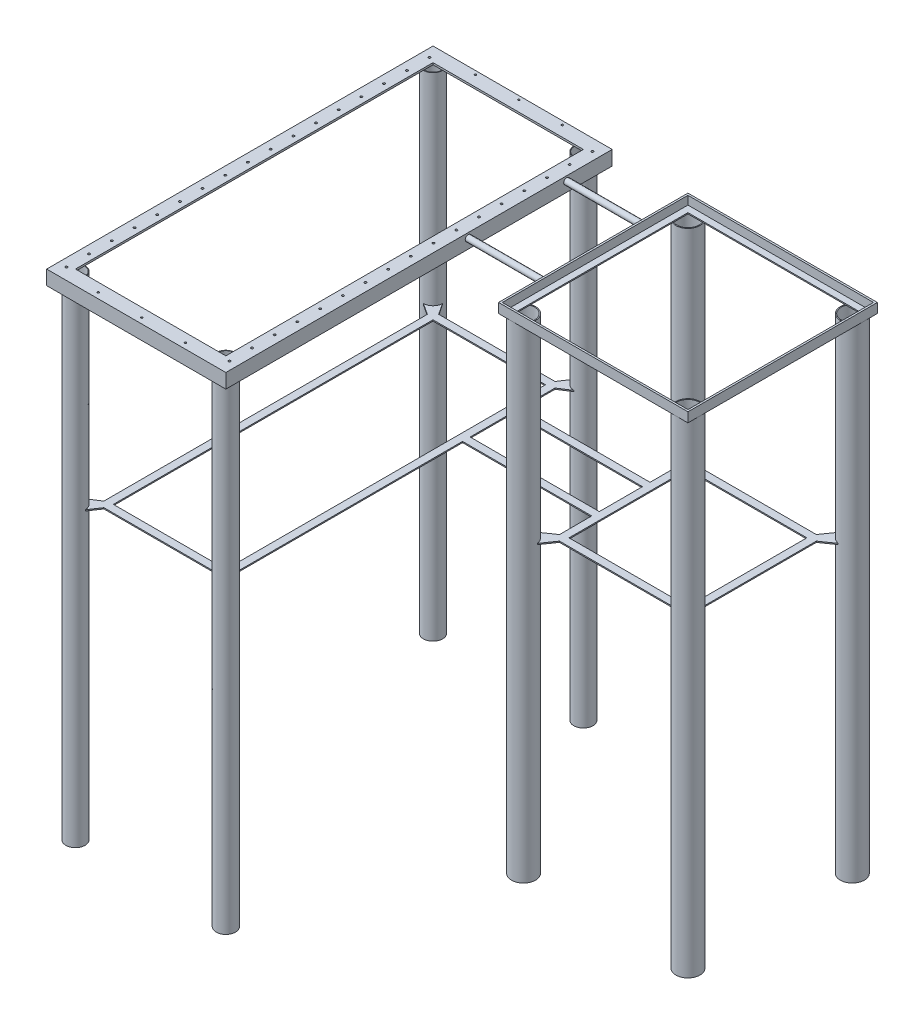
SolidWorks part; units mm, degrees
ref_plane "Alzado" through (0, 0, 0) normal (0, 0, 1) x (1, 0, 0)
ref_plane "Planta" through (0, 0, 0) normal (0, 1, 0) x (1, 0, 0)
ref_plane "Vista lateral" through (0, 0, 0) normal (1, 0, 0) x (0, 0, -1)
sketch "Croquis1" plane through (0, 0, 0) normal (0, 1, 0) x (1, 0, 0)
  line L0 (236.5, 510) -> (-236.5, -510) construction
  line L1 (-236.5, 510) -> (236.5, 510)
  line L2 (-236.5, 510) -> (-236.5, -510)
  line L3 (-236.5, -510) -> (236.5, -510)
  line L4 (236.5, 510) -> (236.5, -510)
  line L6 (-198.5, 472) -> (198.5, 472)
  line L7 (-198.5, 472) -> (-198.5, -472)
  line L8 (-198.5, -472) -> (198.5, -472)
  line L9 (198.5, 472) -> (198.5, -472)
  dimension "D1" = 473
  dimension "D2" = 1020
  dimension "D3" = 38
  dimension "D4" = 38
  dimension "D5" = 38
  dimension "D6" = 38
extrude "Saliente-Extruir1" add sketch "Croquis1" along normal blind 5
sketch "Croquis2" plane through (0, 0, 0) normal (0, -1, 0) x (1, 0, 0)
  line L0 (-231.5, 505) -> (231.5, 505)
  line L1 (231.5, 505) -> (231.5, -505)
  line L2 (231.5, -505) -> (-231.5, -505)
  line L3 (-231.5, -505) -> (-231.5, 505)
  line L4 (-236.5, 510) -> (236.5, 510) construction
  line L5 (-236.5, -510) -> (-236.5, 510) construction
  line L6 (236.5, 510) -> (236.5, -510) construction
  line L7 (236.5, -510) -> (-236.5, -510) construction
  line L8 (-236.5, 510) -> (236.5, 510)
  line L9 (-236.5, -510) -> (-236.5, 510)
  line L10 (236.5, 510) -> (236.5, -510)
  line L11 (236.5, -510) -> (-236.5, -510)
  dimension "D1" = 5
extrude "Saliente-Extruir2" add sketch "Croquis2" along normal blind 33
sketch "Croquis3" plane through (0, 0, 0) normal (0, -1, 0) x (1, 0, 0)
  line L0 (0, -505) -> (0, -413.6353) construction
  line L1 (-231.5, -505) -> (231.5, -505) construction
  line L2 (198.5, 0) -> (-198.5, 0) construction
  line L3 (198.5, 472) -> (198.5, -472) construction
  line L4 (-198.5, -472) -> (-198.5, 472) construction
  circle A0 centre (-198.5, -472) radius 25.4
  circle A1 centre (-198.5, -472) radius 23.9
  circle A2 centre (198.5, -472) radius 23.9
  circle A3 centre (198.5, -472) radius 25.4
  circle A4 centre (-198.5, 472) radius 25.4
  circle A5 centre (-198.5, 472) radius 23.9
  circle A6 centre (198.5, 472) radius 23.9
  circle A7 centre (198.5, 472) radius 25.4
  dimension "D1" = 50.8
  dimension "D2" = 47.8
extrude "Saliente-Extruir3" add sketch "Croquis3" along normal blind 1300
sketch "Croquis4" plane through (0, 0, 0) normal (0, -1, 0) x (1, 0, 0)
  line L0 (236.5, 510) -> (-236.5, 510) construction
  line L1 (-236.5, 510) -> (-236.5, -510) construction
  line L2 (236.5, -510) -> (236.5, 510) construction
  line L12 (168.5, 442) -> (168.5, -442)
  line L13 (168.5, -442) -> (-168.5, -442)
  line L14 (-168.5, -442) -> (-168.5, 442)
  line L15 (-168.5, 442) -> (168.5, 442)
  line L16 (168.5, 442) -> (-168.5, -442) construction
  line L18 (148.5, 422) -> (-148.5, 422)
  line L19 (148.5, 422) -> (148.5, -422)
  line L20 (-236.5, -510) -> (236.5, -510) construction
  line L21 (148.5, -422) -> (-148.5, -422)
  line L22 (-148.5, 422) -> (-148.5, -422)
  dimension "D1" = 68
  dimension "D2" = 20
  dimension "D3" = 68
  dimension "D4" = 68
  dimension "D5" = 68
  dimension "D6" = 20
  dimension "D7" = 20
  dimension "D8" = 20
extrude "Saliente-Extruir4" add sketch "Croquis4" along normal blind 3 from offset 533 separate body
sketch "Croquis5" plane through (0, -533, 0) normal (0, 1, 0) x (1, 0, 0)
  line L0 (153.5, 442) -> (173.1118, 471.2271)
  line L1 (-168.5, 442) -> (168.5, 442) construction
  line L2 (173.1118, 471.2271) -> (181.9129, 457.7456)
  line L3 (181.9129, 457.7456) -> (198.523, 446.6)
  line L4 (198.523, 446.6) -> (168.5, 427)
  line L5 (168.5, 442) -> (168.5, -442) construction
  line L6 (168.5, 427) -> (168.5, 442)
  line L7 (168.5, 442) -> (153.5, 442)
  line L8 (0, 442) -> (0, 371.6421) construction
  line L9 (-168.5, 0) -> (-86.6716, 0) construction
  line L10 (-168.5, -442) -> (-168.5, 442) construction
  line L11 (-198.523, 446.6) -> (-168.5, 427)
  line L12 (-181.9129, 457.7456) -> (-198.523, 446.6)
  line L13 (-173.1118, 471.2271) -> (-181.9129, 457.7456)
  line L14 (-168.5, 427) -> (-168.5, 442)
  line L15 (-168.5, 442) -> (-153.5, 442)
  line L16 (-153.5, 442) -> (-173.1118, 471.2271)
  line L17 (168.5, -442) -> (153.5, -442)
  line L18 (168.5, -427) -> (168.5, -442)
  line L19 (198.523, -446.6) -> (168.5, -427)
  line L20 (181.9129, -457.7456) -> (198.523, -446.6)
  line L21 (173.1118, -471.2271) -> (181.9129, -457.7456)
  line L22 (153.5, -442) -> (173.1118, -471.2271)
  line L23 (-153.5, -442) -> (-173.1118, -471.2271)
  line L24 (-168.5, -442) -> (-153.5, -442)
  line L25 (-168.5, -427) -> (-168.5, -442)
  line L26 (-173.1118, -471.2271) -> (-181.9129, -457.7456)
  line L27 (-181.9129, -457.7456) -> (-198.523, -446.6)
  line L28 (-198.523, -446.6) -> (-168.5, -427)
  arc A0 (173.1, 472) -> (198.5, 446.6) centre (198.5, 472) ccw construction
  dimension "D1" = 15
  dimension "D2" = 15
  dimension "D3" = 16.1
  dimension "D4" = 67
  dimension "D5" = 67
extrude "Saliente-Extruir5" add sketch "Croquis5" against normal blind 3
sketch "Croquis6" plane through (0, 5, 0) normal (0, 1, 0) x (1, 0, 0)
  line L0 (936.5, 510) -> (436.5, 10) construction
  line L1 (436.5, 510) -> (936.5, 510)
  line L2 (436.5, 510) -> (436.5, 10)
  line L3 (436.5, 10) -> (936.5, 10)
  line L4 (936.5, 510) -> (936.5, 10)
  line L5 (-236.5, -510) -> (236.5, -510) construction
  line L7 (458.725, 487.775) -> (914.275, 487.775)
  line L8 (458.725, 487.775) -> (458.725, 32.225)
  line L9 (458.725, 32.225) -> (914.275, 32.225)
  line L10 (914.275, 487.775) -> (914.275, 32.225)
  dimension "D1" = 200
  dimension "D2" = 500
  dimension "D3" = 500
  dimension "D4" = 520
  dimension "D5" = 22.225
  dimension "D6" = 22.225
  dimension "D7" = 22.225
  dimension "D8" = 22.225
extrude "Saliente-Extruir6" add sketch "Croquis6" against normal blind 3 from offset 22.225 separate body
sketch "Croquis7" plane through (0, -20.225, 0) normal (0, -1, 0) x (1, 0, 0)
  line L0 (436.5, -510) -> (436.5, -10) construction
  line L1 (436.5, -10) -> (936.5, -10) construction
  line L2 (936.5, -10) -> (936.5, -510) construction
  line L3 (936.5, -510) -> (436.5, -510) construction
  line L4 (436.5, -510) -> (436.5, -10)
  line L5 (436.5, -10) -> (936.5, -10)
  line L6 (936.5, -10) -> (936.5, -510)
  line L7 (936.5, -510) -> (436.5, -510)
  line L8 (441.5, -505) -> (441.5, -15)
  line L9 (441.5, -15) -> (931.5, -15)
  line L10 (931.5, -15) -> (931.5, -505)
  line L11 (931.5, -505) -> (441.5, -505)
  dimension "D1" = 5
extrude "Saliente-Extruir7" add sketch "Croquis7" against normal blind 25.4
sketch "Croquis9" plane through (436.5, 0, 0) normal (-1, 0, 0) x (0, 0, 1)
  line L0 (-510, -7.525) -> (-10, -7.525) construction
  line L1 (-510, -20.225) -> (-510, 5.175) construction
  line L2 (-10, -20.225) -> (-10, 5.175) construction
  circle A0 centre (-390, -7.525) radius 7.9375
  circle A1 centre (-130, -7.525) radius 7.9375
  dimension "D1" = 15.875
  dimension "D2" = 15.875
  dimension "D3" = 120
  dimension "D4" = 120
extrude "Saliente-Extruir8" add sketch "Croquis9" along normal up to next
sketch "Croquis10" plane through (0, -20.225, 0) normal (0, -1, 0) x (1, 0, 0)
  line L0 (469.5, -10) -> (469.5, -43) construction
  line L1 (436.5, -10) -> (936.5, -10) construction
  line L2 (469.5, -43) -> (436.5, -43) construction
  line L3 (436.5, -510) -> (436.5, -10) construction
  line L4 (458.725, -260) -> (524.3581, -260) construction
  line L5 (458.725, -487.775) -> (458.725, -32.225) construction
  line L7 (914.275, -487.775) -> (458.725, -487.775) construction
  line L8 (686.5, -487.775) -> (686.5, -390.923) construction
  circle A0 centre (469.5, -43) radius 31.75
  circle A1 centre (469.5, -477) radius 31.75
  circle A2 centre (903.5, -477) radius 31.75
  circle A3 centre (903.5, -43) radius 31.75
  circle A4 centre (469.5, -43) radius 29.25
  circle A5 centre (469.5, -477) radius 29.25
  circle A6 centre (903.5, -477) radius 29.25
  circle A7 centre (903.5, -43) radius 29.25
  dimension "D3" = 63.5
  dimension "D4" = 58.5
  dimension "D1" = 33
  dimension "D2" = 33
extrude "Saliente-Extruir9" add sketch "Croquis10" along normal up to surface (1279.775 mm away) up to face at (198.5, -1300, -446.6)
sketch "Croquis11" plane through (0, -533, 0) normal (0, 1, 0) x (1, 0, 0)
  line L1 (469.5, 477) -> (903.5, 477) construction
  line L2 (469.5, 477) -> (469.5, 43) construction
  line L3 (469.5, 43) -> (903.5, 43) construction
  line L4 (903.5, 477) -> (903.5, 43) construction
  line L5 (509.5, 437) -> (863.5, 437)
  line L6 (509.5, 437) -> (509.5, 83)
  line L7 (509.5, 83) -> (863.5, 83)
  line L8 (863.5, 437) -> (863.5, 83)
  line L9 (529.5, 417) -> (843.5, 417)
  line L10 (529.5, 417) -> (529.5, 103)
  line L11 (529.5, 103) -> (843.5, 103)
  line L12 (843.5, 417) -> (843.5, 103)
  dimension "D1" = 40
  dimension "D2" = 40
  dimension "D3" = 40
  dimension "D4" = 20
  dimension "D5" = 20
  dimension "D6" = 20
  dimension "D7" = 20
extrude "Saliente-Extruir10" add sketch "Croquis11" against normal up to vertex (3 mm away) separate body
sketch "Croquis12" plane through (0, -533, 0) normal (0, 1, 0) x (1, 0, 0)
  line L0 (509.5, 422) -> (475.0956, 446.0902)
  line L1 (509.5, 437) -> (509.5, 83) construction
  line L2 (475.0956, 446.0902) -> (491.3466, 453.9611)
  line L3 (491.3466, 453.9611) -> (500.4098, 471.4044)
  line L4 (500.4098, 471.4044) -> (524.5, 437)
  line L5 (863.5, 437) -> (509.5, 437) construction
  line L6 (524.5, 437) -> (509.5, 437)
  line L7 (509.5, 437) -> (509.5, 422)
  line L8 (686.5, 417) -> (686.5, 340.5834) construction
  line L9 (843.5, 417) -> (529.5, 417) construction
  line L10 (863.5, 437) -> (863.5, 422)
  line L11 (529.5, 417) -> (529.5, 103) construction
  line L12 (529.5, 260) -> (598.9729, 260) construction
  line L13 (848.5, 437) -> (863.5, 437)
  line L14 (872.5902, 471.4044) -> (848.5, 437)
  line L15 (881.6534, 453.9611) -> (872.5902, 471.4044)
  line L16 (897.9044, 446.0902) -> (881.6534, 453.9611)
  line L17 (863.5, 422) -> (897.9044, 446.0902)
  line L18 (863.5, 98) -> (897.9044, 73.9098)
  line L19 (897.9044, 73.9098) -> (881.6534, 66.0389)
  line L20 (881.6534, 66.0389) -> (872.5902, 48.5956)
  line L21 (872.5902, 48.5956) -> (848.5, 83)
  line L22 (848.5, 83) -> (863.5, 83)
  line L23 (863.5, 83) -> (863.5, 98)
  line L24 (509.5, 83) -> (509.5, 98)
  line L25 (524.5, 83) -> (509.5, 83)
  line L26 (500.4098, 48.5956) -> (524.5, 83)
  line L27 (491.3466, 66.0389) -> (500.4098, 48.5956)
  line L28 (475.0956, 73.9098) -> (491.3466, 66.0389)
  line L29 (509.5, 98) -> (475.0956, 73.9098)
  line L30 (168.5, 427) -> (168.5, -427) construction
  line L31 (168.5, 337) -> (509.5, 337)
  line L32 (168.5, 337) -> (168.5, 317)
  line L33 (168.5, 317) -> (509.5, 317)
  line L34 (509.5, 337) -> (509.5, 317)
  line L36 (168.5, 203) -> (509.5, 203)
  line L37 (168.5, 203) -> (168.5, 183)
  line L38 (168.5, 183) -> (509.5, 183)
  line L39 (509.5, 203) -> (509.5, 183)
  line L40 (529.5, 103) -> (843.5, 103) construction
  circle A0 centre (469.5, 477) radius 31.75 construction
  dimension "D1" = 55
  dimension "D2" = 55
  dimension "D3" = 42
  dimension "D4" = 42
  dimension "D5" = 15
  dimension "D6" = 15
  dimension "D7" = 20
  dimension "D8" = 20
  dimension "D9" = 80
  dimension "D10" = 80
extrude "Saliente-Extruir11" add sketch "Croquis12" against normal up to vertex
sketch "Esboço1" plane through (0, 5, 0) normal (0, 1, 0) x (1, 0, 0)
  circle A0 centre (-114.9881, -495.2375) radius 2.5
  circle A1 centre (0.0119, -495.2375) radius 2.5
  circle A2 centre (115.0119, -495.2375) radius 2.5
  circle A3 centre (-114.9881, 500.2375) radius 2.5
  circle A4 centre (0.0119, 500.2375) radius 2.5
  circle A5 centre (115.0119, 500.2375) radius 2.5
  dimension "D1" = 5
  dimension "D2" = 5
  dimension "D3" = 5
  dimension "D4" = 5
  dimension "D5" = 5
  dimension "D6" = 5
extrude "Corte-extrusão1" cut sketch "Esboço1" against normal up to next
sketch "Esboço2" plane through (0, 5, 0) normal (0, 1, 0) x (1, 0, 0)
  line L1 (0, -510) -> (0, -370.7931) construction
  line L2 (-236.5, -510) -> (236.5, -510) construction
  circle A0 centre (215.04, -479.28) radius 2.87
  circle A1 centre (215.04, -419.37) radius 2.87
  circle A2 centre (215.04, -359.46) radius 2.87
  circle A3 centre (215.04, -299.55) radius 2.87
  circle A4 centre (215.04, -239.64) radius 2.87
  circle A5 centre (215.04, -179.73) radius 2.87
  circle A6 centre (215.04, -119.82) radius 2.87
  circle A7 centre (215.04, -59.91) radius 2.87
  circle A8 centre (215.04, 0) radius 2.87
  circle A9 centre (215.04, 59.91) radius 2.87
  circle A10 centre (215.04, 119.82) radius 2.87
  circle A11 centre (215.04, 179.73) radius 2.87
  circle A12 centre (215.04, 239.64) radius 2.87
  circle A13 centre (215.04, 299.55) radius 2.87
  circle A14 centre (215.04, 359.46) radius 2.87
  circle A15 centre (215.04, 419.37) radius 2.87
  circle A16 centre (215.04, 479.28) radius 2.87
  circle A17 centre (-215.04, -239.64) radius 2.87
  circle A18 centre (-215.04, -299.55) radius 2.87
  circle A19 centre (-215.04, -359.46) radius 2.87
  circle A20 centre (-215.04, -419.37) radius 2.87
  circle A21 centre (-215.04, -479.28) radius 2.87
  circle A22 centre (-215.04, 479.28) radius 2.87
  circle A23 centre (-215.04, 419.37) radius 2.87
  circle A24 centre (-215.04, 359.46) radius 2.87
  circle A25 centre (-215.04, 299.55) radius 2.87
  circle A26 centre (-215.04, 239.64) radius 2.87
  circle A27 centre (-215.04, 179.73) radius 2.87
  circle A28 centre (-215.04, 119.82) radius 2.87
  circle A29 centre (-215.04, 59.91) radius 2.87
  circle A30 centre (-215.04, 0) radius 2.87
  circle A31 centre (-215.04, -59.91) radius 2.87
  circle A32 centre (-215.04, -119.82) radius 2.87
  circle A33 centre (-215.04, -179.73) radius 2.87
  dimension "D1" = 17
extrude "Corte-extrusão2" cut sketch "Esboço2" against normal up to next (5 mm away)
